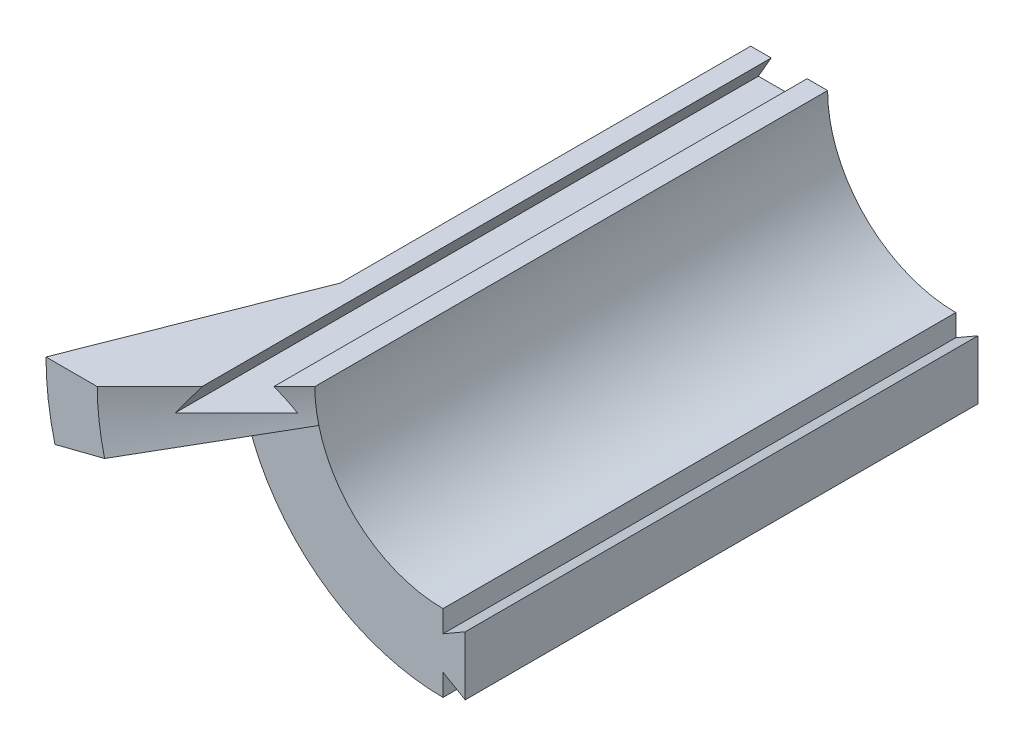
SolidWorks part; units mm, degrees
ref_plane "Front Plane" through (0, 0, 0) normal (0, 0, 1) x (1, 0, 0)
ref_plane "Top Plane" through (0, 0, 0) normal (0, 1, 0) x (1, 0, 0)
ref_plane "Right Plane" through (0, 0, 0) normal (1, 0, 0) x (0, 0, -1)
sketch "Sketch1" plane through (0, 0, 0) normal (0, 0, 1) x (1, 0, 0)
  line L10 (0, 0) -> (0, -25) construction
  line L11 (-40, 0) -> (-25, 0)
  line L12 (0, -25) -> (0, -40)
  line L13 (0, 0) -> (-25, 0) construction
  arc A0 (0, -25) -> (-25, 0) centre (0, 0) cw
  arc A1 (-40, 0) -> (0, -40) centre (0, 0) ccw
  dimension "D1" = 15
  dimension "D2" = 25
extrude "Boss-Extrude2" add sketch "Sketch1" along normal blind 100
sketch "Sketch2" plane through (0, 0, 0) normal (0, 1, 0) x (1, 0, 0)
  line L0 (-25, -100) -> (-46.2132, -121.2132)
  line L1 (-46.2132, -121.2132) -> (-56.2132, -121.2132)
  line L2 (-56.2132, -121.2132) -> (-40, -80)
  line L3 (-40, -100) -> (-40, 0) construction
  line L4 (-25, -100) -> (-40, -100) construction
  line L5 (0, 0) -> (0, -95.3357) construction
  line L6 (-25, -100) -> (-40, -80)
  dimension "D1" = 30
  dimension "D2" = 45
  dimension "D3" = 10
  dimension "D4" = 20
revolve "Revolve1" add sketch "Sketch2" angle 14.32 about L5
sketch "Sketch4" plane through (0, 0, 0) normal (0, 0, -1) x (-1, 0, 0)
  line L0 (25, 0) -> (29, 0)
  line L1 (25, 0) -> (40, 0) construction
  line L2 (29, 0) -> (26.5, -4.3301)
  line L3 (26.5, -4.3301) -> (38.5, -4.3301)
  line L4 (38.5, -4.3301) -> (36, 0)
  line L5 (36, 0) -> (40, 0)
  dimension "D1" = 4
  dimension "D2" = 4
  dimension "D3" = 60
  dimension "D4" = 60
  dimension "D5" = 12
extrude "Cut-Extrude2" cut sketch "Sketch4" against normal through all and the other way through all
sketch "Sketch5" plane through (0, 0, 0) normal (0, 0, -1) x (-1, 0, 0)
  line L0 (0, -25) -> (0, -29.25)
  line L1 (0, -40) -> (0, -25) construction
  line L2 (0, -29.25) -> (-4.3301, -26.75)
  line L3 (-4.3301, -26.75) -> (-4.3301, -38.25)
  line L4 (-4.3301, -38.25) -> (0, -35.75)
  line L5 (0, -35.75) -> (0, -40)
  line L12 (38.5, -4.3301) -> (26.5, -4.3301)
  line L13 (26.5, -4.3301) -> (29, 0)
  line L14 (29, 0) -> (25, 0)
  line L15 (0, -25) -> (0, -40)
  line L16 (40, 0) -> (36, 0)
  line L17 (36, 0) -> (38.5, -4.3301)
  line L21 (0, -25) -> (0, -40)
  arc A2 (0, -25) -> (25, 0) centre (0, 0) ccw
  arc A3 (0, -40) -> (40, 0) centre (0, 0) ccw
  line M18 (0, -25) -> (0, -40)
  dimension "D1" = 4.25
  dimension "D2" = 11.5
  dimension "D3" = 4.25
  dimension "D4" = 60
  dimension "D5" = 60
  dimension "D6" = 0
extrude "Boss-Extrude4" add sketch "Sketch5" against normal blind 100 contours L3 L4 L2 M18
